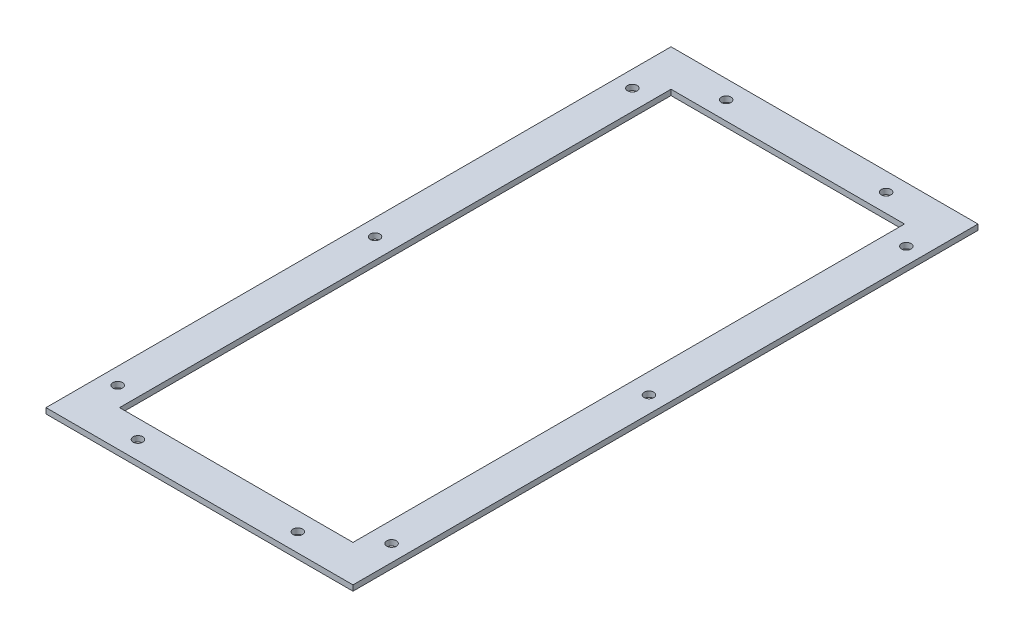
SolidWorks part; units mm, degrees
material "Teak"
ref_plane "Alzado" through (0, 0, 0) normal (0, 0, 1) x (1, 0, 0)
ref_plane "Planta" through (0, 0, 0) normal (0, 1, 0) x (1, 0, 0)
ref_plane "Vista lateral" through (0, 0, 0) normal (1, 0, 0) x (0, 0, -1)
sketch "Croquis1" plane through (0, 0, 0) normal (0, 1, 0) x (1, 0, 0)
  line L0 (-74.5, 170) -> (-74.5, -170) construction
  line L1 (-83.5, 170) -> (83.5, 170)
  line L2 (-83.5, 170) -> (-83.5, -170)
  line L3 (-83.5, -170) -> (83.5, -170)
  line L4 (83.5, 170) -> (83.5, -170)
  line L5 (74.5, 170) -> (74.5, -170) construction
  line L6 (-83.5, 160) -> (83.5, 160) construction
  line L7 (-83.5, -160) -> (83.5, -160) construction
  circle A0 centre (-74.5, 140) radius 2.6
  circle A1 centre (-74.5, 0) radius 2.6
  circle A2 centre (-74.5, -140) radius 2.6
  circle A3 centre (74.5, 140) radius 2.6
  circle A5 centre (74.5, -140) radius 2.6
  circle A6 centre (74.5, 0) radius 2.6
  circle A7 centre (-43.5, 160) radius 2.6
  circle A8 centre (43.5, 160) radius 2.6
  circle A9 centre (-43.5, -160) radius 2.6
  circle A10 centre (43.5, -160) radius 2.6
  point P4 (0, 170)
  point P6 (-83.5, 0)
  dimension "D5" = 5.2
  dimension "D1" = 340
  dimension "D2" = 167
  dimension "D3" = 9
  dimension "D4" = 9
  dimension "D6" = 30
  dimension "D7" = 30
  dimension "D8" = 10
  dimension "D9" = 10
  dimension "D10" = 40
  dimension "D11" = 40
extrude "Saliente-Extruir1" add sketch "Croquis1" along normal blind 3
sketch "Sketch1" plane through (0, 3, 0) normal (0, 1, 0) x (1, 0, 0)
  line L0 (-63.5, 150) -> (-63.5, -150)
  line L1 (-63.5, -150) -> (63.5, -150)
  line L2 (63.5, -150) -> (63.5, 150)
  line L3 (63.5, 150) -> (-63.5, 150)
  line L4 (-83.5, 170) -> (-83.5, -170)
  line L5 (-83.5, -170) -> (83.5, -170)
  line L6 (83.5, -170) -> (83.5, 170)
  line L7 (83.5, 170) -> (-83.5, 170)
  line L8 (-83.5, 170) -> (-83.5, -170)
  line L9 (-83.5, -170) -> (83.5, -170)
  line L10 (83.5, -170) -> (83.5, 170)
  line L11 (83.5, 170) -> (-83.5, 170)
  dimension "D1" = 0
  dimension "D2" = 20
extrude "Cut-Extrude1" cut sketch "Sketch1" against normal blind 10 contours L0 L1 L2 L3
